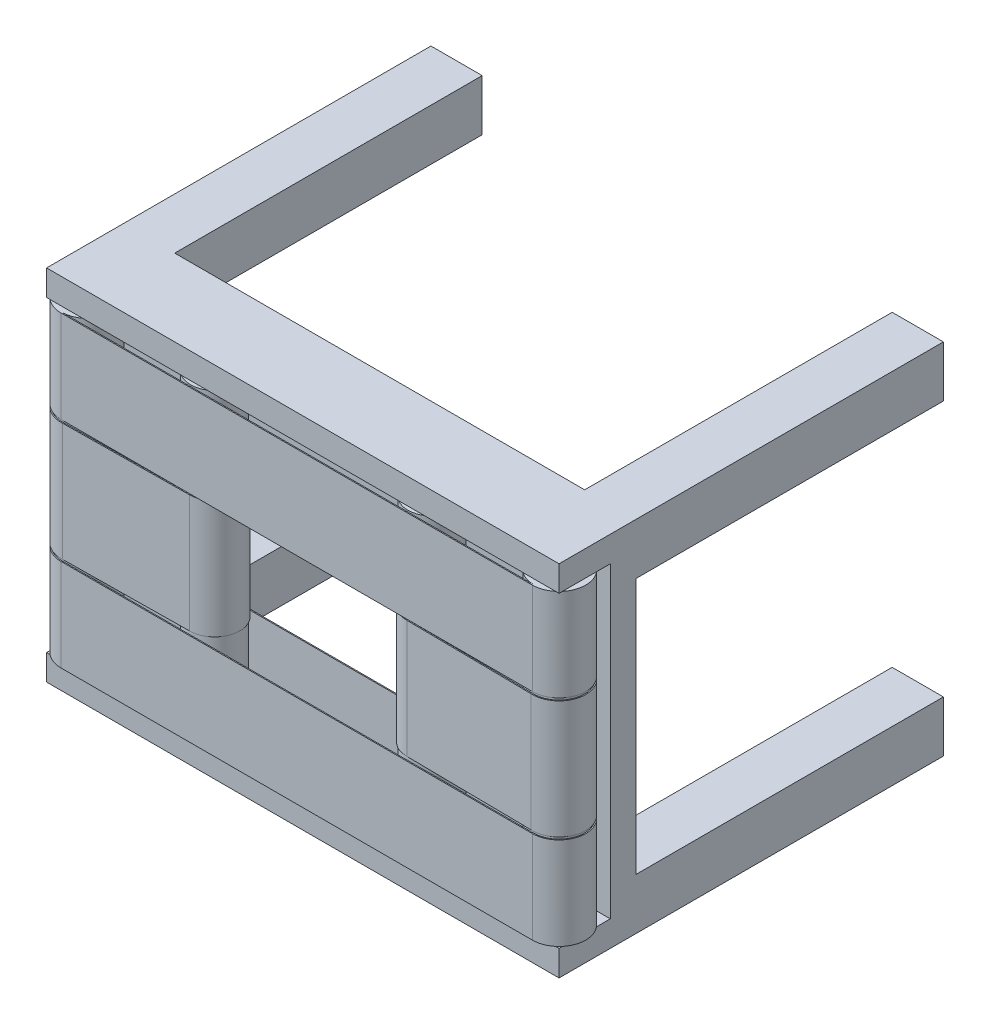
SolidWorks part; units mm, degrees
ref_plane "Front Plane" through (0, 0, 0) normal (0, 0, 1) x (1, 0, 0)
ref_plane "Top Plane" through (0, 0, 0) normal (0, 1, 0) x (1, 0, 0)
ref_plane "Right Plane" through (0, 0, 0) normal (1, 0, 0) x (0, 0, -1)
sketch "Sketch1" plane through (0, 0, 0) normal (0, 0, 1) x (1, 0, 0)
  line L0 (0, 0) -> (-548.4765, 0) construction
  line L1 (0, 0) -> (0, 250) construction
  line L3 (500, -350) -> (-500, -350)
  line L4 (500, -350) -> (500, 350)
  line L5 (500, 350) -> (-500, 350)
  line L6 (-500, -350) -> (-500, 350)
  line L7 (500, -350) -> (-500, 350) construction
  line L8 (500, 350) -> (-500, -350) construction
  line L9 (450, -300) -> (-450, -300)
  line L10 (450, -300) -> (450, 300)
  line L11 (450, 300) -> (-450, 300)
  line L12 (-450, -300) -> (-450, 300)
  line L13 (450, -300) -> (-450, 300) construction
  line L14 (450, 300) -> (-450, -300) construction
  dimension "D1" = 700
  dimension "D2" = 1000
  dimension "D3" = 50
  dimension "D4" = 50
extrude "Boss-Extrude1" add sketch "Sketch1" along normal blind 150
sketch "Sketch2" plane through (500, 0, 0) normal (1, 0, 0) x (0, 0, -1)
  line L0 (-150, -350) -> (-150, 350) construction
  line L1 (-150, 300) -> (-50, 300)
  line L2 (-150, 300) -> (-150, -300)
  line L3 (-150, -300) -> (-50, -300)
  line L4 (-50, 300) -> (-50, -300)
  line L10 (-150, 350) -> (0, 350) construction
  line L12 (-150, -350) -> (0, -350) construction
  dimension "D1" = 50
  dimension "D2" = 50
  dimension "D3" = 100
extrude "Cut-Extrude1" cut sketch "Sketch2" against normal blind 1000
sketch "Sketch3" plane through (0, 300, 0) normal (0, -1, 0) x (1, 0, 0)
  line L0 (500, 150) -> (-500, 150) construction
  line L1 (500, 50) -> (500, 150) construction
  circle A0 centre (460, 110) radius 50
  dimension "D1" = 100
  dimension "D2" = 40
  dimension "D3" = 40
extrude "Boss-Extrude2" add sketch "Sketch3" along normal blind 600
mirror "Mirror1" about plane through (0, 0, 0) normal (1, 0, 0) of "Boss-Extrude2"
sketch "Sketch4" plane through (0, -300, 0) normal (0, -1, 0) x (1, 0, 0)
  line L0 (-460, 160) -> (460, 160)
  line L1 (-460, 162) -> (460, 162)
  line L2 (460, 60) -> (-460, 60)
  line L3 (460, 58) -> (-460, 58)
  arc A0 (460, 60) -> (460, 160) centre (460, 110) ccw
  arc A1 (-460, 160) -> (-460, 60) centre (-460, 110) ccw
  arc A2 (460, 58) -> (460, 162) centre (460, 110) ccw
  arc A3 (-460, 162) -> (-460, 58) centre (-460, 110) ccw
  dimension "D1" = 2
extrude "Boss-Extrude3" add sketch "Sketch4" against normal blind 180
mirror "Mirror2" about plane through (0, 0, 0) normal (0, 1, 0) of "Boss-Extrude3"
sketch "Sketch5" plane through (0, 0, 0) normal (0, 0, -1) x (-1, 0, 0)
  line L0 (0, 350) -> (0, 0) construction
  line L1 (-500, 350) -> (-400, 350)
  line L2 (-500, 350) -> (-500, 250)
  line L3 (-500, 250) -> (-400, 250)
  line L4 (-400, 350) -> (-400, 250)
  line L5 (-500, 350) -> (500, 350) construction
  line L6 (0, 0) -> (510, 0) construction
  line L7 (510, -120) -> (510, 120) construction
  line L8 (500, 250) -> (400, 250)
  line L9 (400, 350) -> (400, 250)
  line L10 (500, 350) -> (400, 350)
  line L11 (500, 350) -> (500, 250)
  line L12 (500, -350) -> (500, -250)
  line L13 (500, -350) -> (400, -350)
  line L14 (400, -350) -> (400, -250)
  line L15 (500, -250) -> (400, -250)
  line L16 (-500, -250) -> (-400, -250)
  line L17 (-400, -350) -> (-400, -250)
  line L18 (-500, -350) -> (-400, -350)
  line L19 (-500, -350) -> (-500, -250)
  dimension "D1" = 100
  dimension "D2" = 100
extrude "Boss-Extrude4" add sketch "Sketch5" along normal blind 600
sketch "Sketch7" plane through (0, 300, 0) normal (0, -1, 0) x (1, 0, 0)
  line L0 (-512, 110) -> (512, 110) construction
  arc A0 (-500, 143.2265) -> (-500, 76.7735) centre (-460, 110) ccw construction
  arc A1 (500, 76.7735) -> (500, 143.2265) centre (460, 110) ccw construction
  circle A2 centre (-212, 110) radius 47
  dimension "D1" = 94
  dimension "D2" = 300
extrude "Boss-Extrude15" add sketch "Sketch7" along normal blind 600
sketch "Sketch10" plane through (0, 0, 0) normal (0, 1, 0) x (1, 0, 0)
  line L6 (-212, -157) -> (-456.8994, -159.9038)
  line L8 (-456.8994, -60.0962) -> (-212, -63)
  line L9 (-211.988, -159) -> (-456.826, -161.903)
  line L10 (-456.826, -58.097) -> (-211.988, -61)
  arc A8 (-456.8994, -60.0962) -> (-456.8994, -159.9038) centre (-460, -110) ccw
  arc A9 (-212, -157) -> (-212, -63) centre (-212, -110) ccw
  arc A10 (-456.826, -58.097) -> (-456.826, -161.903) centre (-460, -110) ccw
  arc A11 (-211.988, -159) -> (-211.988, -61) centre (-212, -110) ccw
  dimension "D1" = 2
extrude "Boss-Extrude16" add sketch "Sketch10" along normal mid plane 230
mirror "Mirror3" about plane through (0, 0, 0) normal (1, 0, 0) of "Boss-Extrude15", "Boss-Extrude16"
